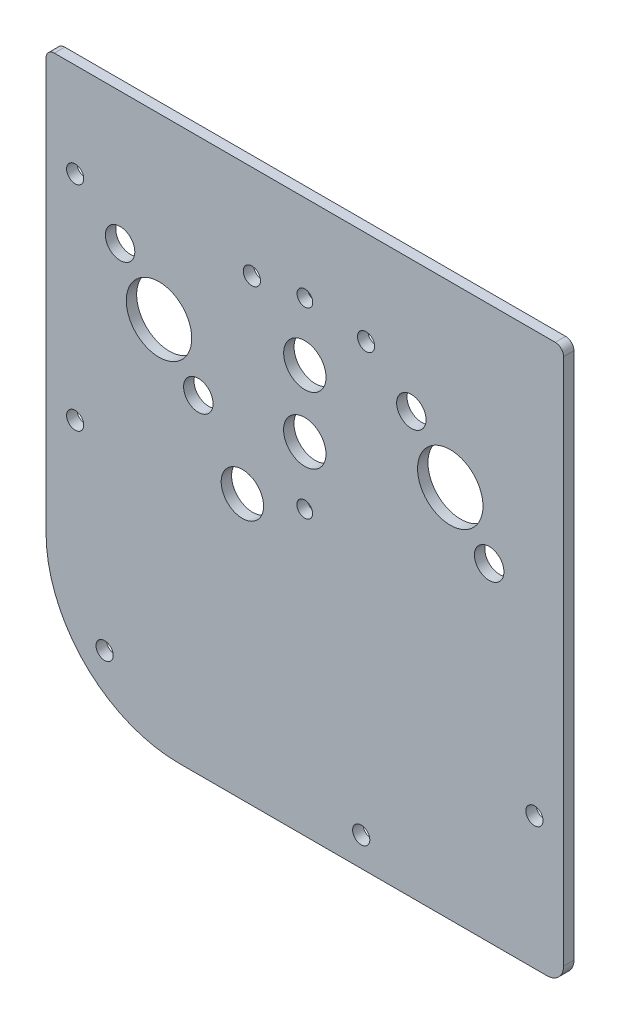
SolidWorks part; units mm, degrees
material "Alloy Steel"
ref_plane "X-Y Datum" through (0, 0, 0) normal (0, 0, 1) x (1, 0, 0)
ref_plane "X-Z Datum" through (0, 0, 0) normal (0, 1, 0) x (1, 0, 0)
ref_plane "Y-Z Datum" through (0, 0, 0) normal (1, 0, 0) x (0, 0, -1)
sketch "Sketch2" plane through (0, 0, 0) normal (0, 0, 1) x (1, 0, 0)
  line L0 (-16.6627, 125.3723) -> (128.7807, 125.3723)
  line L1 (135.1307, 119.0223) -> (135.1307, -19.4077)
  line L2 (130.0507, -24.4877) -> (17.6273, -24.4877)
  line L3 (-23.0127, 16.1523) -> (-23.0127, 119.0223)
  line L4 (127.9913, 129.8343) -> (127.9913, 50.0171) construction
  line L5 (127.9913, 129.8343) -> (-15.891, 129.8343) construction
  line L6 (-15.891, 129.8343) -> (-15.891, 50.0171) construction
  line L7 (127.9913, 50.0171) -> (-15.891, 50.0171) construction
  line L8 (127.9913, 129.8343) -> (-15.891, 50.0171) construction
  line L9 (-15.891, 129.8343) -> (127.9913, 50.0171) construction
  line L10 (100.509, 89.979) -> (86.3372, 78.0874) construction
  line L11 (86.3372, 78.0874) -> (114.6809, 101.8706) construction
  line L12 (11.564, 89.9787) -> (25.7804, 101.8169) construction
  line L13 (11.564, 89.9787) -> (-2.563, 78.034) construction
  line L14 (100.509, 89.979) -> (88.6175, 104.1508) construction
  line L15 (88.6175, 104.1508) -> (112.4006, 75.8072) construction
  line L16 (11.564, 89.9787) -> (-0.3904, 104.0975) construction
  line L17 (-0.3904, 104.0975) -> (23.5185, 75.8599) construction
  circle A0 centre (-14.1227, 115.6573) radius 2.625
  arc A1 (17.6273, -24.4877) -> (-23.0127, 16.1523) centre (17.6273, 16.1523) cw
  arc A2 (128.7807, 125.3723) -> (135.1307, 119.0223) centre (128.7807, 119.0223) cw
  arc A3 (-16.6627, 125.3723) -> (-23.0127, 119.0223) centre (-16.6627, 119.0223) ccw
  arc A4 (135.1307, -19.4077) -> (130.0507, -24.4877) centre (130.0507, -19.4077) cw
  circle A5 centre (100.509, 89.979) radius 27.5 construction
  circle A6 centre (56.0501, 79.7923) radius 6.477
  circle A7 centre (56.0346, 62.0123) radius 2.4
  circle A8 centre (56.0679, 100.1123) radius 6.477
  circle A9 centre (56.0834, 117.8923) radius 2.4
  circle A10 centre (11.564, 89.9787) radius 27.5 construction
  circle A11 centre (36.9798, 56.4941) radius 6.477
  circle A13 centre (39.8806, 115.6573) radius 2.625
  circle A14 centre (74.7774, 115.7106) radius 2.625
  circle A16 centre (-14.1227, 50.4423) radius 2.625
  circle A17 centre (-5.1243, -6.0163) radius 2.625
  circle A18 centre (73.2964, -15.5977) radius 2.625
  circle A19 centre (126.2407, 15.9468) radius 2.625
  circle A20 centre (11.5011, 89.9257) radius 27.5 construction
  circle A21 centre (100.509, 89.979) radius 27.5 construction
  circle A27 centre (11.5011, 89.9257) radius 10
  circle A28 centre (11.5928, 71.4257) radius 4.5 construction
  circle A29 centre (12.964, 108.4257) radius 4.5 construction
  circle A30 centre (100.509, 89.979) radius 10
  circle A31 centre (100.4929, 71.479) radius 4.5 construction
  circle A32 centre (100.5252, 108.479) radius 4.5 construction
  circle A33 centre (11.564, 89.9787) radius 18.5 construction
  circle A34 centre (100.509, 89.979) radius 18.5 construction
  circle A35 centre (86.3372, 78.0874) radius 4.5 construction
  circle A37 centre (114.6809, 101.8706) radius 4.5 construction
  circle A38 centre (25.7804, 101.8169) radius 4.5 construction
  circle A39 centre (-2.563, 78.034) radius 4.5 construction
  circle A40 centre (88.6175, 104.1508) radius 4.5
  circle A41 centre (112.4006, 75.8072) radius 4.5
  circle A42 centre (-0.3904, 104.0975) radius 4.5
  circle A43 centre (23.5185, 75.8599) radius 4.5
  dimension "D1" = 40.64
  dimension "D2" = 6.35
  dimension "D3" = 5.08
  dimension "D4" = 37
  dimension "D5" = 37
  dimension "D6" = 37
extrude "Boss-Extrude1" add sketch "Sketch2" along normal blind 3.175
sketch "Sketch3" plane through (0, 0, 3.175) normal (0, 0, 1) x (1, 0, 0)
  line L0 (-23.0127, 119.0223) -> (-23.0127, 144.4223)
  line L1 (-23.0127, 144.4223) -> (135.1307, 144.4223)
  line L2 (135.1307, 119.0223) -> (135.1307, 144.4223)
  line L3 (-16.6627, 125.3723) -> (128.7807, 125.3723)
  arc A0 (-23.0127, 119.0223) -> (-16.6627, 125.3723) centre (-16.6627, 119.0223) cw
  arc A1 (128.7807, 125.3723) -> (135.1307, 119.0223) centre (128.7807, 119.0223) cw
extrude "Boss-Extrude2" add sketch "Sketch3" against normal blind 3.175
fillet "Fillet1" radius 2.54 2 edges at (-23.0127, 144.4223, 1.5875) (135.1307, 144.4223, 1.5875)
